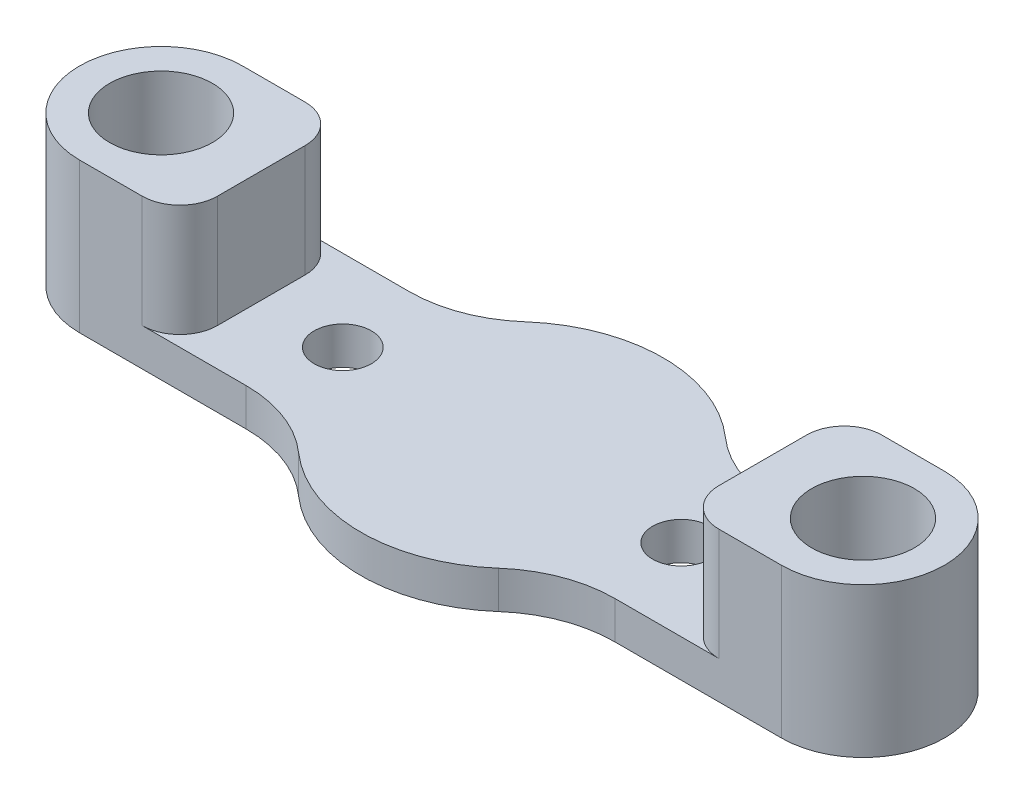
SolidWorks part; units mm, degrees
material "Custom Plastic"
ref_plane "Front Plane" through (0, 0, 0) normal (0, 0, 1) x (1, 0, 0)
ref_plane "Top Plane" through (0, 0, 0) normal (0, 1, 0) x (1, 0, 0)
ref_plane "Right Plane" through (0, 0, 0) normal (1, 0, 0) x (0, 0, -1)
sketch "Sketch1" plane through (0, 0, 0) normal (0, 1, 0) x (1, 0, 0)
  line L0 (-1000, 0) -> (49000, 0) construction
  line L1 (0, -1000) -> (0, 49000) construction
  line L2 (-7.3514, 3.25) -> (-14, 3.25)
  line L3 (-7.3514, -3.25) -> (-14, -3.25)
  line L4 (7.3514, -3.25) -> (14, -3.25)
  line L5 (7.3514, 3.25) -> (14, 3.25)
  circle A1 centre (-6.75, 0) radius 1.14
  arc A5 (3.99, 4.5211) -> (-3.99, 4.5211) centre (0, 0) ccw
  arc A6 (-7.3514, 3.25) -> (-3.99, 4.5211) centre (-7.3514, 8.33) ccw
  circle A17 centre (-14, 0) radius 2.05
  arc A18 (-14, 3.25) -> (-14, -3.25) centre (-14, 0) ccw
  arc A19 (3.99, -4.5211) -> (-3.99, -4.5211) centre (0, 0) cw
  arc A20 (-7.3514, -3.25) -> (-3.99, -4.5211) centre (-7.3514, -8.33) cw
  arc A21 (7.3514, 3.25) -> (3.99, 4.5211) centre (7.3514, 8.33) cw
  arc A22 (7.3514, -3.25) -> (3.99, -4.5211) centre (7.3514, -8.33) ccw
  circle A23 centre (6.75, 0) radius 1.14
  circle A24 centre (14, 0) radius 2.05
  arc A25 (14, 3.25) -> (14, -3.25) centre (14, 0) cw
  dimension "D1" = 6.03
  dimension "D3" = 2.28
  dimension "D4" = 5.08
  dimension "D6" = 4.1
  dimension "D8" = 6.5
  dimension "D2" = 13.5
  dimension "D7" = 28
extrude "Boss-Extrude2" add sketch "Sketch1" along normal blind 1.5
sketch "Sketch2" plane through (0, 1.5, 0) normal (0, 1, 0) x (1, 0, 0)
  line L0 (0, -1000) -> (0, 49000) construction
  line L1 (-14, 3.25) -> (-10, 3.25)
  line L2 (-7.3514, 3.25) -> (-14, 3.25) construction
  line L3 (-10, 3.25) -> (-10, -3.25)
  line L4 (-14, -3.25) -> (-7.3514, -3.25) construction
  line L5 (-10, -3.25) -> (-14, -3.25)
  line L6 (10, -3.25) -> (14, -3.25)
  line L7 (10, 3.25) -> (10, -3.25)
  line L8 (14, 3.25) -> (10, 3.25)
  arc A0 (-14, 3.25) -> (-14, -3.25) centre (-14, 0) ccw
  circle A2 centre (-14, 0) radius 2.05 construction
  circle A3 centre (-14, 0) radius 2.05
  circle A4 centre (14, 0) radius 2.05
  arc A5 (14, 3.25) -> (14, -3.25) centre (14, 0) cw
  dimension "D1" = 4
extrude "Boss-Extrude3" add sketch "Sketch2" along normal blind 4.47
fillet "Fillet1" radius 1.5 4 edges at (10, 3.735, 3.25) (10, 3.735, -3.25) (-10, 3.735, 3.25) (-10, 3.735, -3.25)
